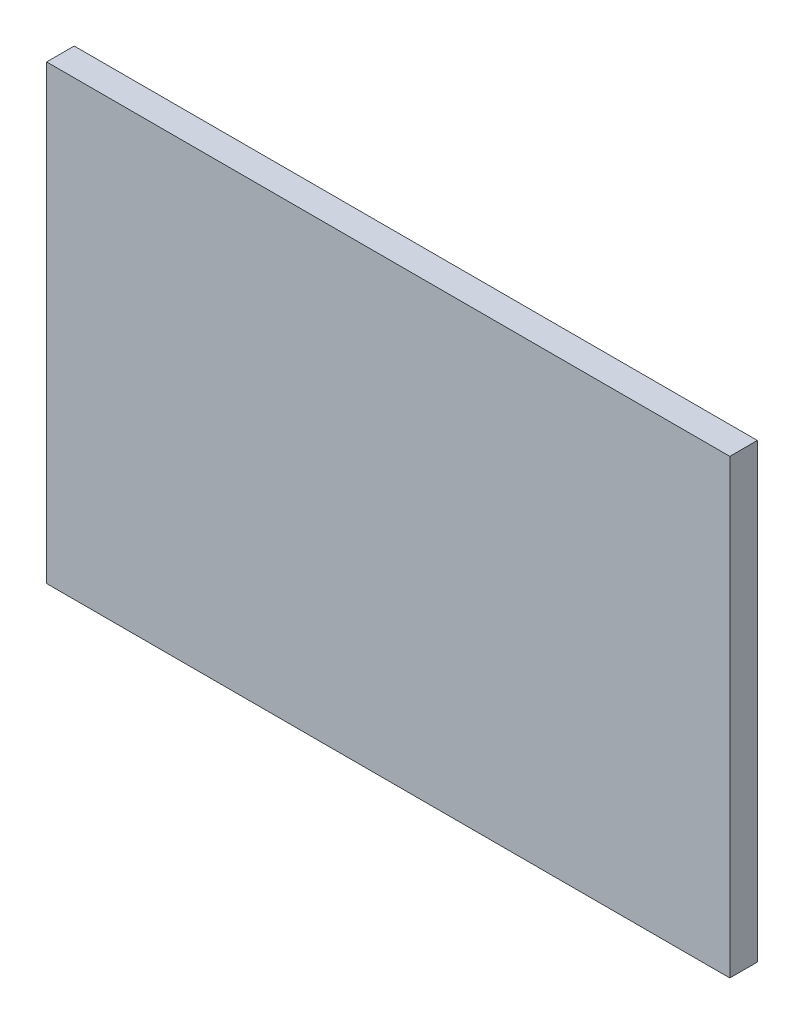
SolidWorks part; units mm, degrees
ref_plane "Front Plane" through (0, 0, 0) normal (0, 0, 1) x (1, 0, 0)
ref_plane "Top Plane" through (0, 0, 0) normal (0, 1, 0) x (1, 0, 0)
ref_plane "Right Plane" through (0, 0, 0) normal (1, 0, 0) x (0, 0, -1)
sketch "Sketch1" plane through (0, 0, 0) normal (0, 0, 1) x (1, 0, 0)
  line L1 (-62, 41) -> (62, 41)
  line L2 (-62, 41) -> (-62, -41)
  line L3 (-62, -41) -> (62, -41)
  line L4 (62, 41) -> (62, -41)
  dimension "D1" = 124
  dimension "D2" = 82
  dimension "D3" = 41
  dimension "D4" = 62
extrude "Boss-Extrude1" add sketch "Sketch1" along normal blind 5
